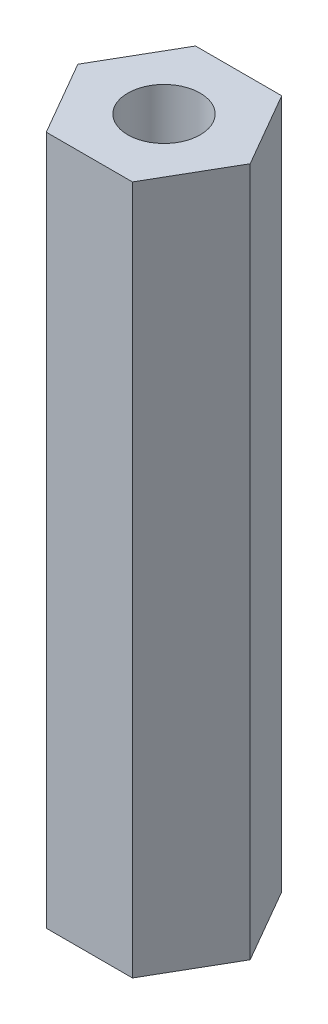
SolidWorks part; units mm, degrees
ref_plane "Front Plane" through (0, 0, 0) normal (0, 0, 1) x (1, 0, 0)
ref_plane "Top Plane" through (0, 0, 0) normal (0, 1, 0) x (1, 0, 0)
ref_plane "Right Plane" through (0, 0, 0) normal (1, 0, 0) x (0, 0, -1)
sketch "Sketch1" plane through (0, 0, 0) normal (0, 1, 0) x (1, 0, 0)
  line L1 (5, 0) -> (2.5, 4.3301)
  line L2 (2.5, 4.3301) -> (-2.5, 4.3301)
  line L3 (-2.5, 4.3301) -> (-5, 0)
  line L4 (-5, 0) -> (-2.5, -4.3301)
  line L5 (-2.5, -4.3301) -> (2.5, -4.3301)
  line L6 (2.5, -4.3301) -> (5, 0)
  circle A0 centre (0, 0) radius 2.1
  circle A1 centre (0, 0) radius 4.3301 construction
  dimension "D1" = 4.2
  dimension "D2" = 5
extrude "Boss-Extrude1" add sketch "Sketch1" along normal blind 40
ref_plane "Plane1" through (0, 20, 0) normal (0, 1, 0) x (1, 0, 0)
sketch "Sketch2" plane through (0, 20, 0) normal (0, 1, 0) x (1, 0, 0)
  circle A0 centre (0, 0) radius 2.1 construction
  circle A1 centre (0, 0) radius 2.1
extrude "Boss-Extrude3" add sketch "Sketch2" along normal offset from surface 6 and the other way offset from surface (14 mm away) 6 up to face at (0, 40, 0) other way up to face at (0, 0, 0)
